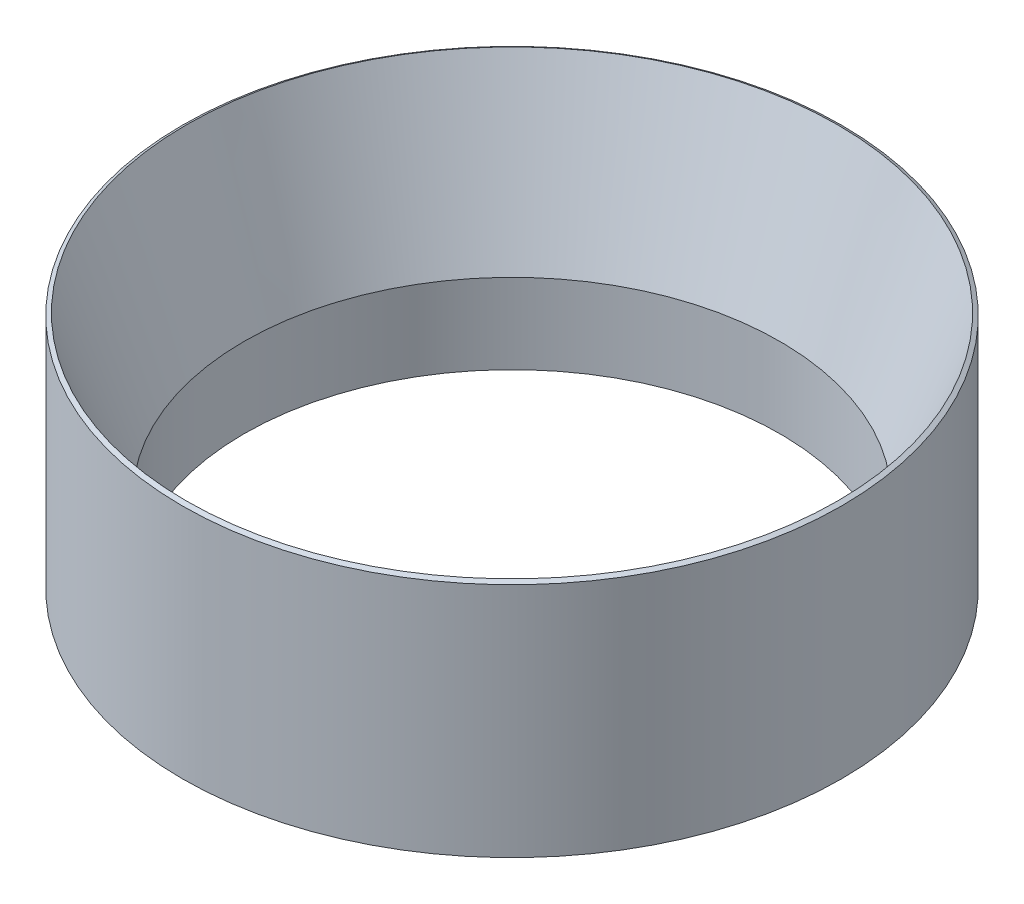
SolidWorks part; units mm, degrees
ref_plane "Front Plane" through (0, 0, 0) normal (0, 0, 1) x (1, 0, 0)
ref_plane "Top Plane" through (0, 0, 0) normal (0, 1, 0) x (1, 0, 0)
ref_plane "Right Plane" through (0, 0, 0) normal (1, 0, 0) x (0, 0, -1)
sketch "Sketch1" plane through (0, 0, 0) normal (0, 0, 1) x (1, 0, 0)
  line L0 (0, 0) -> (42.545, 0) construction
  line L3 (42.545, 12.7) -> (51.7144, 37.8927)
  line L4 (52.3494, 37.5261) -> (52.3494, 0)
  line L6 (52.3494, 0) -> (42.545, 0)
  line L7 (0, 39.6374) -> (0, 0) construction
  line L8 (0, 39.6374) -> (52.3494, 39.6374) construction
  line L9 (42.545, 12.7) -> (42.545, 39.6374) construction
  line L10 (51.7144, 37.8927) -> (52.3494, 37.5261)
  line L11 (51.7144, 37.8927) -> (52.3494, 39.6374) construction
  line L12 (52.3494, 39.6374) -> (52.3494, 37.5261) construction
  line L13 (42.545, 12.7) -> (42.545, 0)
  line L19 (42.545, 12.7) -> (42.545, 10.16) construction
  dimension "D1" = 60
  dimension "D2" = 42.545
  dimension "D3" = 20
  dimension "D4" = 52.3494
  dimension "D6" = 12.7
  dimension "D7" = 2.54
  dimension "0.25" = 0.635
revolve "Revolve1" add sketch "Sketch1" angle 360 about L7
